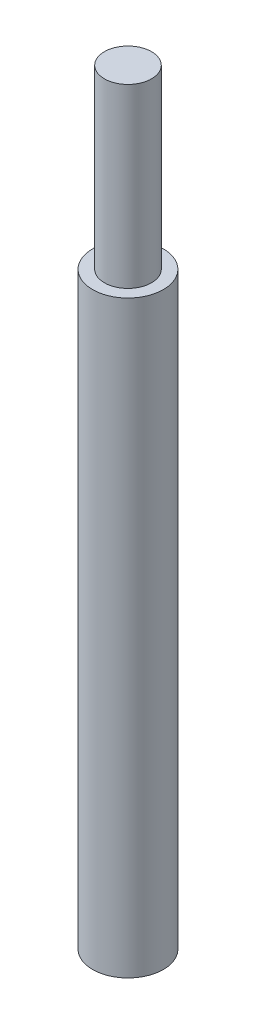
SolidWorks part; units mm, degrees
material "AISI 304"
ref_plane "Front Plane" through (0, 0, 0) normal (0, 0, 1) x (1, 0, 0)
ref_plane "Top Plane" through (0, 0, 0) normal (0, 1, 0) x (1, 0, 0)
ref_plane "Right Plane" through (0, 0, 0) normal (1, 0, 0) x (0, 0, -1)
other "Configuration Table"
sketch "Sketch1" plane through (0, 0, 0) normal (0, 1, 0) x (1, 0, 0)
  circle A0 centre (0, 0) radius 3
  dimension "D1" = 6
extrude "Steel_Tube" add sketch "Sketch1" along normal blind 50
sketch "Sketch2" plane through (0, 0, 0) normal (0, 1, 0) x (1, 0, 0)
  circle A0 centre (0, 0) radius 2
  dimension "D1" = 4
extrude "Cable_Stub" add sketch "Sketch2" along normal blind 15 from offset 50
equation "\"Jar_OD\"= 90  'ASSUMED - Part G fallback - jar outer diameter"
equation "\"Jar_H\"= 120  'ASSUMED - Part G fallback - jar height"
equation "\"Pump_L\"= 45  'ASSUMED - Part G fallback"
equation "\"Pump_W\"= 24  'ASSUMED - Part G fallback"
equation "\"Pump_H\"= 33  'ASSUMED - Part G fallback"
equation "\"Pump_Outlet_OD\"= 7.5  'ASSUMED - Part G fallback"
equation "\"Tube_OD\"= 8  'ASSUMED - Part G fallback"
equation "\"Tube_ID\"= 6  'ASSUMED - Part G fallback"
equation "\"TDS_Body_Dia\"= 12  'ASSUMED - Part G fallback"
equation "\"TDS_Wet_Len\"= 45  'ASSUMED - Part G fallback - length in water"
equation "\"DS_Tube_Dia\"= 6  'ASSUMED - Part G fallback"
equation "\"DS_Tube_Len\"= 50  'ASSUMED - Part G fallback"
equation "\"ORP_Body_Dia\"= 12  'ASSUMED - Part G fallback"
equation "\"ORP_Body_Len\"= 150  'ASSUMED - Part G fallback"
equation "\"ORP_Cap_Dia\"= 16  'ASSUMED - Part G fallback"
equation "\"Turb_W\"= 33  'ASSUMED - Part G fallback - head width"
equation "\"Turb_D\"= 28  'ASSUMED - Part G fallback - head depth"
equation "\"Turb_H\"= 30  'ASSUMED - Part G fallback - head height"
equation "\"Turb_Slot_W\"= 10  'ASSUMED - Part G fallback - slot width"
equation "\"Flow_L\"= 62  'ASSUMED - Part G fallback YF-S201"
equation "\"Flow_W\"= 36  'ASSUMED - Part G fallback"
equation "\"Flow_H\"= 35  'ASSUMED - Part G fallback"
equation "\"Thread_G12_OD\"= 20.955  'ASSUMED - Part G fallback thread G1/2 (major diameter)"
equation "\"Valve_L\"= 75  'ASSUMED - Part G fallback"
equation "\"Valve_W\"= 45  'ASSUMED - Part G fallback"
equation "\"Valve_H\"= 60  'ASSUMED - Part G fallback"
equation "\"Tee_L\"= 40  'ASSUMED - Part G fallback - overall length"
equation "\"Tee_Branch_L\"= 25  'ASSUMED - Part G fallback"
equation "\"Tee_OD\"= 12  'ASSUMED - Part G fallback"
equation "\"Cuv_W\"= 12.5  'ASSUMED - old R3 cuvette (station suppressed in SS4)"
equation "\"Cuv_D\"= 12.5  'ASSUMED - old R3 cuvette (station suppressed in SS4)"
equation "\"Cuv_H\"= 45  'ASSUMED - old R3 cuvette (station suppressed in SS4)"
equation "\"LED_Board_L\"= 20  'ASSUMED - Part G fallback"
equation "\"LED_Board_W\"= 20  'ASSUMED - Part G fallback - LED at centre"
equation "\"GUVA_L\"= 20  'ASSUMED - Part G fallback"
equation "\"GUVA_W\"= 12  'ASSUMED - Part G fallback - sensor at centre"
equation "\"Reed_L\"= 27  'ASSUMED - Part G fallback MC-38 half"
equation "\"Reed_W\"= 14  'ASSUMED - Part G fallback"
equation "\"Reed_H\"= 8  'ASSUMED - Part G fallback"
equation "\"ESP_L\"= 51  'ASSUMED - Part G fallback"
equation "\"ESP_W\"= 28  'ASSUMED - Part G fallback"
equation "\"TFT_L\"= 58  'ASSUMED - Part G fallback - board"
equation "\"TFT_W\"= 35  'ASSUMED - Part G fallback - board"
equation "\"TFT_Win_L\"= 35  'ASSUMED - Part G fallback - visible window"
equation "\"TFT_Win_W\"= 28  'ASSUMED - Part G fallback - visible window"
equation "\"Relay_L\"= 50  'ASSUMED - Part G fallback"
equation "\"Relay_W\"= 26  'ASSUMED - Part G fallback"
equation "\"Relay_H\"= 19  'ASSUMED - Part G fallback"
equation "\"Mosfet_L\"= 34  'ASSUMED - Part G fallback"
equation "\"Mosfet_W\"= 17  'ASSUMED - Part G fallback"
equation "\"Mosfet_H\"= 12  'ASSUMED - Part G fallback"
equation "\"TDS_Board_L\"= 42  'ASSUMED - Part G fallback"
equation "\"TDS_Board_W\"= 32  'ASSUMED - Part G fallback"
equation "\"Turb_Board_L\"= 38  'ASSUMED - Part G fallback"
equation "\"Turb_Board_W\"= 28  'ASSUMED - Part G fallback"
equation "\"BNC_Thread_Dia\"= 9.5  'ASSUMED - Part G fallback"
equation "\"Plate_L\"= 420  'ASSUMED - Part G fallback"
equation "\"Plate_W\"= 297  'ASSUMED - Part G fallback"
equation "\"Plate_T\"= 6  'ASSUMED - Part G fallback"
equation "\"Probe_Clr\"= 0.3  'DESIGN VALUE - Part C rule 3 - printed probe hole = diameter + 0.3"
equation "\"Cuv_Clr\"= 0.2  'DESIGN VALUE - Part C rule 3 - cuvette pocket = size + 0.2"
equation "\"Label_H\"= 0.6  'DESIGN VALUE - Part D - raised label height"
equation "\"D1@Sketch1\" = \"DS_Tube_Dia\""
equation "\"D1@Steel_Tube\" = \"DS_Tube_Len\""
equation "\"Booster_L\"= 150  'ASSUMED - Part G fallback - booster pump"
equation "\"Booster_W\"= 95  'ASSUMED - Part G fallback"
equation "\"Booster_H\"= 100  'ASSUMED - Part G fallback"
equation "\"PTube_OD\"= 6.35  'ASSUMED - Part G fallback - product tube 1/4 inch"
equation "\"Qz_Out\"= 12  'ASSUMED - Part G fallback - quartz channel outside square"
equation "\"Qz_Path\"= 10  'ASSUMED - Part G fallback - quartz channel inside light path"
equation "\"Qz_L\"= 40  'ASSUMED - Part G fallback - quartz channel length"
equation "\"LED860_Dia\"= 5  'ASSUMED - Part G fallback - 860 nm LED"
equation "\"BPW_L\"= 5.4  'ASSUMED - Part G fallback - BPW34"
equation "\"BPW_W\"= 4.3  'ASSUMED - Part G fallback - BPW34"
equation "\"Cart_Dia\"= 50  'ASSUMED - Part G fallback - sediment and pre-carbon cartridges"
equation "\"Cart_L\"= 255  'ASSUMED - Part G fallback"
equation "\"UF_Dia\"= 50  'ASSUMED - Part G fallback - UF cartridge"
equation "\"UF_L\"= 260  'ASSUMED - Part G fallback"
equation "\"RO_Dia\"= 62  'ASSUMED - Part G fallback - RO membrane housing"
equation "\"RO_L\"= 300  'ASSUMED - Part G fallback"
equation "\"UVC_Dia\"= 40  'ASSUMED - Part G fallback - UV-C chamber"
equation "\"UVC_L\"= 300  'ASSUMED - Part G fallback"
equation "\"Tank_W\"= 260  'ASSUMED - Part G fallback - storage tank"
equation "\"Tank_D\"= 160  'ASSUMED - Part G fallback"
equation "\"Tank_H\"= 300  'ASSUMED - Part G fallback"
equation "\"Cab_W\"= 400  'ASSUMED - Part G fallback - purifier cabinet"
equation "\"Cab_D\"= 270  'ASSUMED - Part G fallback"
equation "\"Cab_H\"= 560  'ASSUMED - Part G fallback"
equation "\"ORP_Board_L\"= 40  'ASSUMED - Part G fallback - ORP buffer board"
equation "\"ORP_Board_W\"= 30  'ASSUMED - Part G fallback"
equation "\"Opt_Board_L\"= 50  'ASSUMED - Part G fallback - optical front-end board"
equation "\"Opt_Board_W\"= 40  'ASSUMED - Part G fallback"
equation "\"Buck_L\"= 43  'ASSUMED - Part G fallback - 12 V to 5 V buck module"
equation "\"Buck_W\"= 21  'ASSUMED - Part G fallback"
equation "\"Buck_H\"= 14  'ASSUMED - Part G fallback"
equation "\"BB_L\"= 165  'ASSUMED - Part G fallback - breadboard (As_Built_R3 only)"
equation "\"BB_W\"= 55  'ASSUMED - Part G fallback"
equation "\"BB_H\"= 10  'ASSUMED - Part G fallback"
